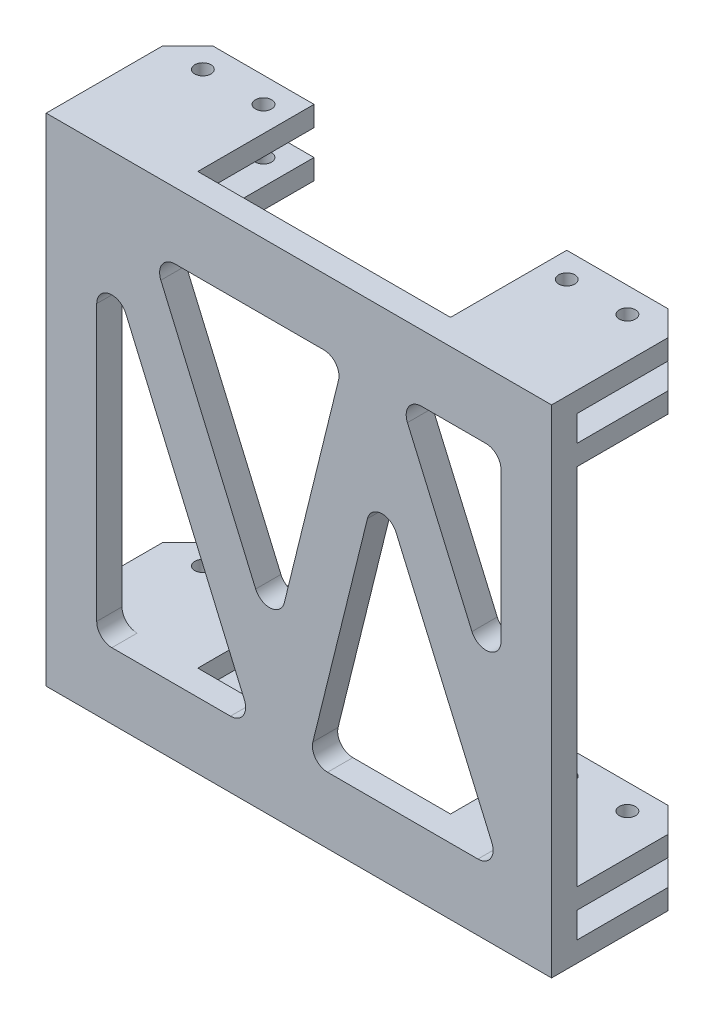
SolidWorks part; units mm, degrees
ref_plane "前视基准面" through (0, 0, 0) normal (0, 0, 1) x (1, 0, 0)
ref_plane "上视基准面" through (0, 0, 0) normal (0, 1, 0) x (1, 0, 0)
ref_plane "右视基准面" through (0, 0, 0) normal (1, 0, 0) x (0, 0, -1)
sketch "草图1" plane through (0, 0, 0) normal (0, 0, 1) x (1, 0, 0)
  line L0 (-158.1257, 0) -> (-266.6901, 0) construction
  line L1 (-260.8862, 4.1) -> (-160.8862, 4.1)
  line L2 (-260.8862, 4.1) -> (-260.8862, -94.1)
  line L3 (-260.8862, -94.1) -> (-160.8862, -94.1)
  line L4 (-160.8862, 4.1) -> (-160.8862, -94.1)
  line L5 (-158.1257, -90) -> (-266.6901, -90) construction
  line L6 (-245.1311, -22.3584) -> (-221.6706, -76.813)
  line L7 (-235.4386, -9) -> (-205.9533, -9)
  line L8 (-250.8862, -23.5454) -> (-250.8862, -78)
  line L9 (-247.8862, -81) -> (-224.4257, -81)
  line L10 (-170.8862, -12) -> (-170.8862, -41.4233)
  line L11 (-203.0405, -12.7178) -> (-213.7689, -56.2546)
  line L12 (-219.4369, -56.7238) -> (-238.1938, -13.187)
  line L13 (-235.4386, -9) -> (-212.1706, -9)
  line L15 (-208.1237, -77.2796) -> (-197.3201, -33.6026)
  line L16 (-191.6557, -33.1289) -> (-172.7059, -76.806)
  line L17 (-158.1257, -5) -> (-266.6901, -5) construction
  line L18 (-158.1257, -85) -> (-266.6901, -85) construction
  line L19 (-176.6384, -42.6174) -> (-189.404, -13.194)
  line L20 (-186.6519, -9) -> (-173.8862, -9)
  line L21 (-205.2115, -81) -> (-175.458, -81)
  arc A0 (-173.8862, -9) -> (-170.8862, -12) centre (-173.8862, -12) cw
  arc A1 (-189.404, -13.194) -> (-186.6519, -9) centre (-186.6519, -12) cw
  arc A2 (-176.6384, -42.6174) -> (-170.8862, -41.4233) centre (-173.8862, -41.4233) ccw
  arc A3 (-172.7059, -76.806) -> (-175.458, -81) centre (-175.458, -78) cw
  arc A4 (-208.1237, -77.2796) -> (-205.2115, -81) centre (-205.2115, -78) ccw
  arc A5 (-191.6557, -33.1289) -> (-197.3201, -33.6026) centre (-194.4078, -34.323) ccw
  arc A6 (-203.0405, -12.7178) -> (-205.9533, -9) centre (-205.9533, -12) ccw
  arc A7 (-238.1938, -13.187) -> (-235.4386, -9) centre (-235.4386, -12) cw
  arc A8 (-213.7689, -56.2546) -> (-219.4369, -56.7238) centre (-216.6817, -55.5368) cw
  arc A9 (-221.6706, -76.813) -> (-224.4257, -81) centre (-224.4257, -78) cw
  arc A10 (-250.8862, -78) -> (-247.8862, -81) centre (-247.8862, -78) ccw
  arc A11 (-245.1311, -22.3584) -> (-250.8862, -23.5454) centre (-247.8862, -23.5454) ccw
  point P27 (0, 0)
  point P28 (0, 0)
  point P33 (-191.2237, -9)
  point P40 (-209.044, -81)
  dimension "D8" = 3
  dimension "D1" = 100
  dimension "D2" = 4.1
  dimension "D3" = 4.1
  dimension "D4" = 4
  dimension "D5" = 10
  dimension "D6" = 4
  dimension "D7" = 10
  dimension "D9" = 10
  dimension "D10" = 10
extrude "凸台-拉伸1" add sketch "草图1" along normal blind 5 contours L4 L1 L2 L3 A11 L6 A9 L9 A10 L8 A5 L16 A3 L21 A4 L15 A2 L19 A1 L20 A0 L10 L11 A8 L12 A7 L7 A6
sketch "草图2" plane through (0, 0, 0) normal (0, 0, -1) x (-1, 0, 0)
  line L0 (260.8862, 4.1) -> (260.8862, -94.1) construction
  line L1 (260.8862, 4.1) -> (235.8862, 4.1)
  line L2 (260.8862, 4.1) -> (260.8862, 0.1)
  line L3 (260.8862, 0.1) -> (235.8862, 0.1)
  line L4 (235.8862, 4.1) -> (235.8862, 0.1)
  line L5 (260.8862, -9) -> (235.8862, -9)
  line L6 (260.8862, -9) -> (260.8862, -5)
  line L7 (260.8862, -5) -> (235.8862, -5)
  line L8 (235.8862, -9) -> (235.8862, -5)
  line L9 (210.8862, 4.1) -> (210.8862, -94.1) construction
  line L10 (260.8862, 4.1) -> (160.8862, 4.1) construction
  line L11 (260.8862, -94.1) -> (160.8862, -94.1) construction
  line L12 (260.8862, -45) -> (160.8862, -45) construction
  line L13 (160.8862, 4.1) -> (160.8862, -94.1) construction
  line L14 (185.8862, -9) -> (185.8862, -5)
  line L15 (160.8862, -5) -> (185.8862, -5)
  line L16 (160.8862, -9) -> (160.8862, -5)
  line L17 (160.8862, -9) -> (185.8862, -9)
  line L18 (185.8862, 4.1) -> (185.8862, 0.1)
  line L19 (160.8862, 0.1) -> (185.8862, 0.1)
  line L20 (160.8862, 4.1) -> (160.8862, 0.1)
  line L21 (160.8862, 4.1) -> (185.8862, 4.1)
  line L22 (160.8862, -94.1) -> (185.8862, -94.1)
  line L23 (160.8862, -94.1) -> (160.8862, -90.1)
  line L24 (160.8862, -90.1) -> (185.8862, -90.1)
  line L25 (185.8862, -94.1) -> (185.8862, -90.1)
  line L26 (160.8862, -81) -> (185.8862, -81)
  line L27 (160.8862, -81) -> (160.8862, -85)
  line L28 (160.8862, -85) -> (185.8862, -85)
  line L29 (185.8862, -81) -> (185.8862, -85)
  line L30 (235.8862, -81) -> (235.8862, -85)
  line L31 (260.8862, -85) -> (235.8862, -85)
  line L32 (260.8862, -81) -> (260.8862, -85)
  line L33 (260.8862, -81) -> (235.8862, -81)
  line L34 (235.8862, -94.1) -> (235.8862, -90.1)
  line L35 (260.8862, -90.1) -> (235.8862, -90.1)
  line L36 (260.8862, -94.1) -> (260.8862, -90.1)
  line L37 (260.8862, -94.1) -> (235.8862, -94.1)
  dimension "D1" = 4
  dimension "D2" = 5.1
  dimension "D3" = 25
  dimension "D4" = 25
  dimension "D5" = 4
extrude "凸台-拉伸2" add sketch "草图2" along normal blind 23
chamfer "倒角1" distance 5 angle 45 8 edges at (-260.8862, -92.1, -23) (-260.8862, -83, -23) (-160.8862, -83, -23) (-160.8862, -92.1, -23) (-160.8862, -7, -23) (-160.8862, 2.1, -23) (-260.8862, -7, -23) (-260.8862, 2.1, -23)
sketch "草图3" plane through (0, 4.1, 0) normal (0, 1, 0) x (1, 0, 0)
  line L0 (-255.8862, 23) -> (-235.8862, 23) construction
  line L1 (-185.8862, 23) -> (-165.8862, 23) construction
  line L2 (-235.8862, 23) -> (-235.8862, 0) construction
  line L4 (-185.8862, 23) -> (-185.8862, 0) construction
  circle A0 centre (-252.8862, 18) radius 1.6
  circle A1 centre (-240.8862, 18) radius 1.6
  circle A2 centre (-180.8862, 18) radius 1.6
  circle A3 centre (-168.8862, 18) radius 1.6
  dimension "D1" = 3.2
  dimension "D2" = 5
  dimension "D3" = 5
  dimension "D4" = 5
  dimension "D5" = 5
  dimension "D6" = 5
  dimension "D7" = 12
  dimension "D8" = 5
  dimension "D9" = 12
extrude "切除-拉伸1" cut sketch "草图3" against normal blind 100
